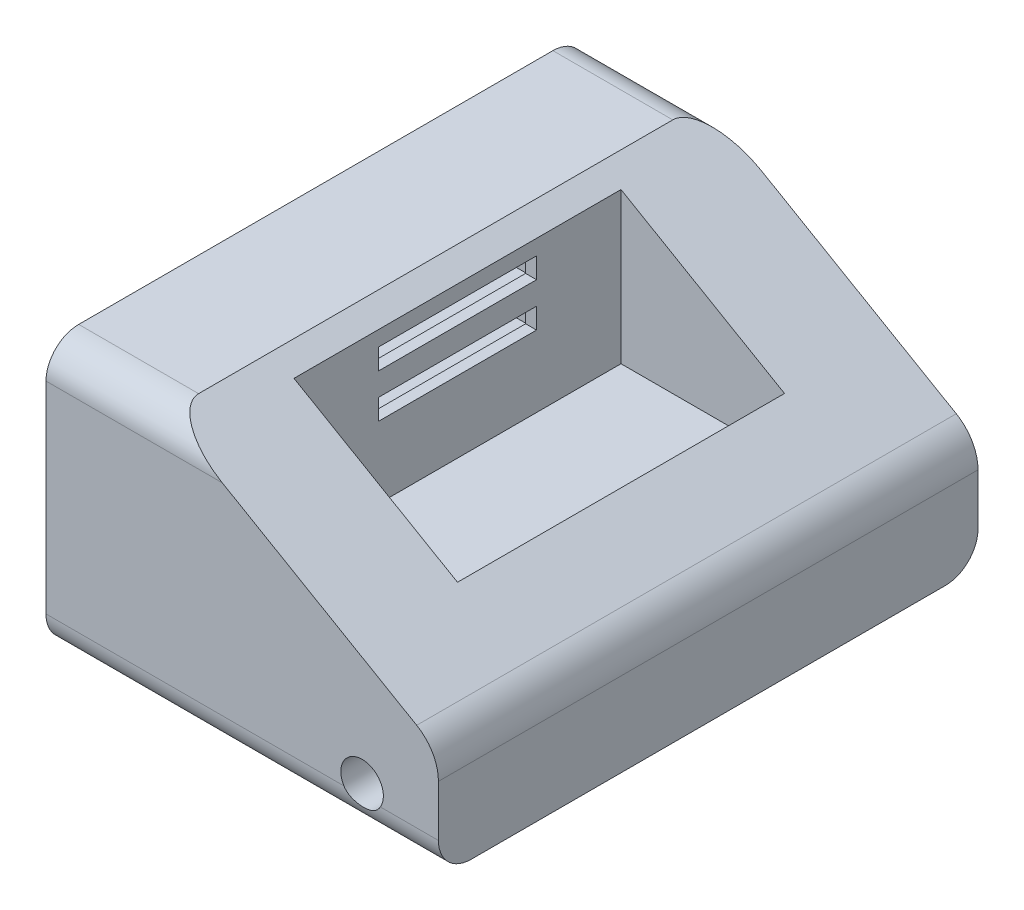
SolidWorks part; units mm, degrees
ref_plane "Спереди" through (0, 0, 0) normal (0, 0, 1) x (1, 0, 0)
ref_plane "Сверху" through (0, 0, 0) normal (0, 1, 0) x (1, 0, 0)
ref_plane "Справа" through (0, 0, 0) normal (1, 0, 0) x (0, 0, -1)
sketch "Эскиз1" plane through (0, 0, 0) normal (1, 0, 0) x (0, 0, -1)
  line L0 (-1050, 0) -> (48950, 0) construction
  line L1 (0, -1021.7777) -> (0, 48978.2223) construction
  line L2 (-24.75, -12.25) -> (24.75, -12.25)
  line L3 (-24.75, -12.25) -> (-24.75, 12.25)
  line L4 (-24.75, 12.25) -> (24.75, 12.25)
  line L5 (24.75, -12.25) -> (24.75, 12.25)
  line L6 (-24.75, -12.25) -> (24.75, 12.25) construction
  line L7 (-24.75, 12.25) -> (24.75, -12.25) construction
  point P3 (0, 0)
  dimension "D1" = 24.5
  dimension "D2" = 49.5
extrude "Бобышка-Вытянуть1" add sketch "Эскиз1" along normal blind 36
sketch "Эскиз2" plane through (0, 0, 0) normal (-1, 0, 0) x (0, 0, 1)
  line L1 (-24.75, -12.25) -> (-24.75, 12.25) construction
  line L2 (24.75, 12.25) -> (24.75, -12.25) construction
  line L3 (24.75, -12.25) -> (-24.75, -12.25) construction
  circle A0 centre (-20, -7.25) radius 2.5
  circle A1 centre (20, -7.25) radius 2.5
  dimension "D3" = 5
  dimension "D1" = 5
  dimension "D2" = 4.75
  dimension "D4" = 4.75
  dimension "D5" = 5
extrude "Вырез-Вытянуть1" cut sketch "Эскиз2" against normal blind 3
sketch "Эскиз3" plane through (0, 0, 0) normal (-1, 0, 0) x (0, 0, 1)
  line L0 (0, -1000) -> (0, 49000) construction
  line L1 (-7.6, 3.5) -> (7.6, 3.5)
  line L2 (-7.6, 7.5) -> (7.6, 7.5)
  line L3 (-7.6, 7.5) -> (-7.6, 10)
  line L4 (-7.6, 10) -> (7.6, 10)
  line L5 (7.6, 7.5) -> (7.6, 10)
  line L6 (-7.6, 7.5) -> (7.6, 10) construction
  line L7 (-7.6, 10) -> (7.6, 7.5) construction
  line L8 (-24.75, 12.25) -> (24.75, 12.25) construction
  line L9 (-7.6, 3.5) -> (-7.6, 6)
  line L10 (-7.6, 6) -> (7.6, 6)
  line L11 (7.6, 3.5) -> (7.6, 6)
  line L12 (-7.6, 3.5) -> (7.6, 6) construction
  line L13 (-7.6, 6) -> (7.6, 3.5) construction
  point P1 (0, 8.75)
  point P10 (0, 0)
  point P11 (0, 4.75)
  point P16 (0, 4.7462)
  point P24 (0, 0)
  dimension "D1" = 15.2
  dimension "D2" = 2.5
  dimension "D3" = 2.25
  dimension "D4" = 2.5
  dimension "D5" = 4
extrude "Вырез-Вытянуть2" cut sketch "Эскиз3" against normal blind 12
fillet "Скругление1" radius 3 4 edges at (18, 12.25, -24.75) (18, -12.25, -24.75) (18, 12.25, 24.75) (18, -12.25, 24.75)
sketch "Эскиз5" plane through (0, 0, 0) normal (0, 0, 1) x (1, 0, 0)
  line L0 (36, -12.25) -> (36, -9.25) construction
  line L3 (36, -12.25) -> (0, -12.25) construction
  circle A0 centre (29, -8.25) radius 1.95
  dimension "D1" = 3.9
  dimension "D2" = 7
  dimension "D3" = 4
extrude "Вырез-Вытянуть3" cut sketch "Эскиз5" against normal through all both and the other way through all
sketch "Эскиз6" plane through (0, 0, -24.75) normal (0, 0, -1) x (-1, 0, 0)
  circle A0 centre (-29, -8.25) radius 4
  dimension "D1" = 8
extrude "Вырез-Вытянуть4" cut sketch "Эскиз6" against normal blind 3 and the other way through all
sketch "Эскиз7" plane through (0, 0, 0) normal (0, 0, 1) x (1, 0, 0)
  line L1 (24, -12.25) -> (34, -12.25)
  line L2 (24, -12.25) -> (24, -3.25)
  line L3 (24, -3.25) -> (34, -3.25)
  line L4 (34, -12.25) -> (34, -3.25)
  line L5 (24, -12.25) -> (34, -3.25) construction
  line L6 (24, -3.25) -> (34, -12.25) construction
  line L7 (36, -12.25) -> (36, -9.25) construction
  line L9 (36, -12.25) -> (0, -12.25) construction
  point P4 (29, -7.75)
  point P5 (34, 12.0531)
  point P9 (24, -12.25)
  dimension "D1" = 7
  dimension "D2" = 10
  dimension "D3" = 9
extrude "Вырез-Вытянуть5" cut sketch "Эскиз7" against normal mid plane 15
sketch "Эскиз8" plane through (0, 0, -24.75) normal (0, 0, -1) x (-1, 0, 0)
  line L0 (-11, 12.25) -> (-36, -2.25)
  line L3 (-36, -2.25) -> (-36, 12.25)
  line L4 (-36, 12.25) -> (-11, 12.25)
  line L8 (-36, 12.25) -> (0, 12.25) construction
  line L9 (0, -12.25) -> (-29, -12.25) construction
  point P2 (-35, 7.9051)
  point P3 (-35, 12.25)
  point P4 (-9.3014, 4.0039)
  point P5 (-10.1329, 12.25)
  dimension "D1" = 10
  dimension "D2" = 25
extrude "Вырез-Вытянуть6" cut sketch "Эскиз8" against normal through all
fillet "Скругление2" radius 4 1 edges at (36, -2.25, 0)
sketch "Эскиз9" plane through (0, 12.25, 0) normal (0, -1, 0) x (1, 0, 0)
  line L0 (-1000, 0) -> (49000, 0) construction
  line L2 (13, -15) -> (28, -15)
  line L3 (13, -15) -> (13, 15)
  line L4 (13, 15) -> (28, 15)
  line L5 (28, -15) -> (28, 15)
  line L6 (13, -15) -> (28, 15) construction
  line L7 (13, 15) -> (28, -15) construction
  line L9 (0, 21.75) -> (0, -21.75) construction
  point P1 (20.5, 0)
  dimension "D1" = 13
  dimension "D2" = 15
  dimension "D3" = 30
extrude "Вырез-Вытянуть7" cut sketch "Эскиз9" along normal blind 15
sketch "Эскиз11" plane through (12, 0, 0) normal (-1, 0, 0) x (0, 0, 1)
  line L0 (-1007.6, 8.75) -> (48992.4, 8.75) construction
  line L1 (-7.25, 9.7) -> (7.25, 9.7)
  line L2 (-7.25, 9.7) -> (-7.25, 7.8)
  line L3 (-7.25, 7.8) -> (7.25, 7.8)
  line L4 (7.25, 9.7) -> (7.25, 7.8)
  line L5 (-7.25, 9.7) -> (7.25, 7.8) construction
  line L6 (-7.25, 7.8) -> (7.25, 9.7) construction
  line L7 (-7.6, 10) -> (-7.6, 7.5) construction
  line L8 (-1007.6, 4.75) -> (48992.4, 4.75) construction
  line L9 (-7.6, 6) -> (-7.6, 3.5) construction
  line L10 (0, -990) -> (0, 49010) construction
  line L11 (7.6, 10) -> (-7.6, 10) construction
  line L13 (-7.25, 5.7) -> (7.25, 5.7)
  line L14 (-7.25, 5.7) -> (-7.25, 3.8)
  line L15 (-7.25, 3.8) -> (7.25, 3.8)
  line L16 (7.25, 5.7) -> (7.25, 3.8)
  line L17 (-7.25, 5.7) -> (7.25, 3.8) construction
  line L18 (-7.25, 3.8) -> (7.25, 5.7) construction
  point P0 (0, 8.75)
  point P10 (-7.6, 8.75)
  point P15 (-7.6, 4.75)
  point P16 (0, 4.75)
  point P20 (0, 10)
  point P25 (0, 4.75)
  dimension "D1" = 1.9
  dimension "D2" = 14.5
  dimension "D3" = 1.9
extrude "Вырез-Вытянуть8" cut sketch "Эскиз11" against normal blind 2
